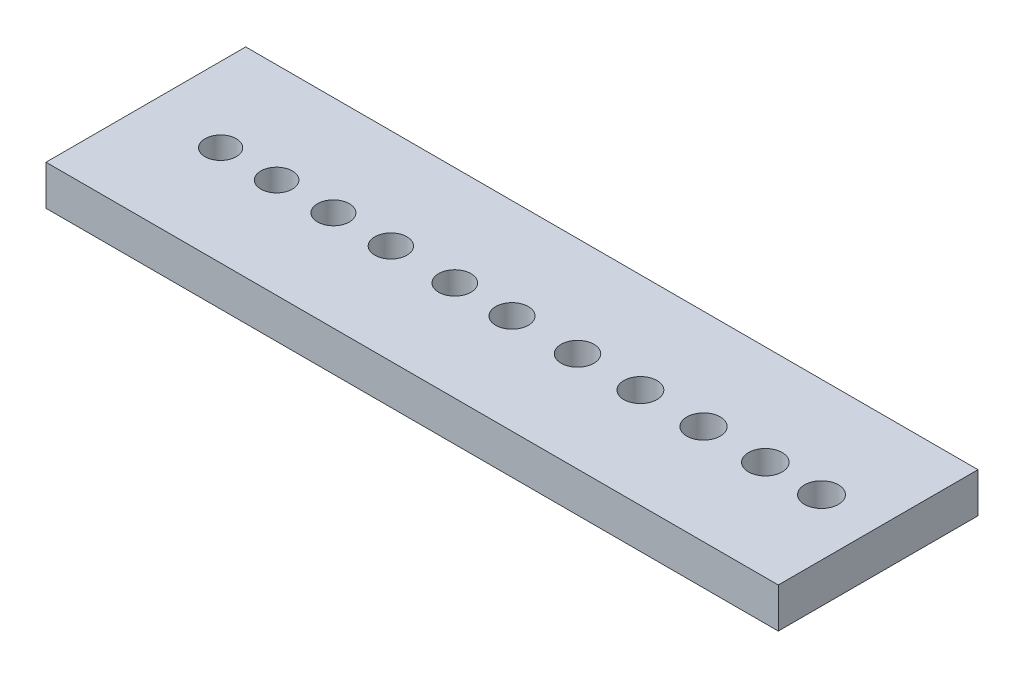
SolidWorks part; units mm, degrees
ref_plane "Alzado" through (0, 0, 0) normal (0, 0, 1) x (1, 0, 0)
ref_plane "Planta" through (0, 0, 0) normal (0, 1, 0) x (1, 0, 0)
ref_plane "Vista lateral" through (0, 0, 0) normal (1, 0, 0) x (0, 0, -1)
sketch "Croquis1" plane through (0, 0, 0) normal (0, 1, 0) x (1, 0, 0)
  line L0 (-27.5, 0) -> (27.5, 0) construction
  line L1 (-27.5, -7.5) -> (27.5, -7.5)
  line L2 (-27.5, -7.5) -> (-27.5, 7.5)
  line L3 (-27.5, 7.5) -> (27.5, 7.5)
  line L4 (27.5, -7.5) -> (27.5, 7.5)
  line L5 (-27.5, -7.5) -> (27.5, 7.5) construction
  line L6 (-27.5, 7.5) -> (27.5, -7.5) construction
  circle A0 centre (-21.8854, 0) radius 1.175
  circle A1 centre (-17.6786, 0) radius 1.185
  circle A2 centre (-13.4135, 0) radius 1.195
  circle A3 centre (-9.0995, 0) radius 1.205
  circle A4 centre (-4.2952, 0) radius 1.215
  circle A5 centre (0, 0) radius 1.225
  circle A6 centre (4.9213, 0) radius 1.235
  circle A7 centre (9.6437, 0) radius 1.245
  circle A8 centre (14.3865, 0) radius 1.255
  circle A9 centre (19.0286, 0) radius 1.265
  circle A10 centre (23.2453, 0) radius 1.275
  point P26 (23.2453, 0)
  dimension "D3" = 2.35
  dimension "D4" = 2.37
  dimension "D5" = 2.39
  dimension "D6" = 2.41
  dimension "D7" = 2.43
  dimension "D8" = 2.45
  dimension "D9" = 2.47
  dimension "D10" = 2.49
  dimension "D11" = 2.51
  dimension "D12" = 2.53
  dimension "D13" = 2.55
  dimension "D1" = 55
  dimension "D2" = 15
extrude "Saliente-Extruir1" add sketch "Croquis1" along normal blind 3
